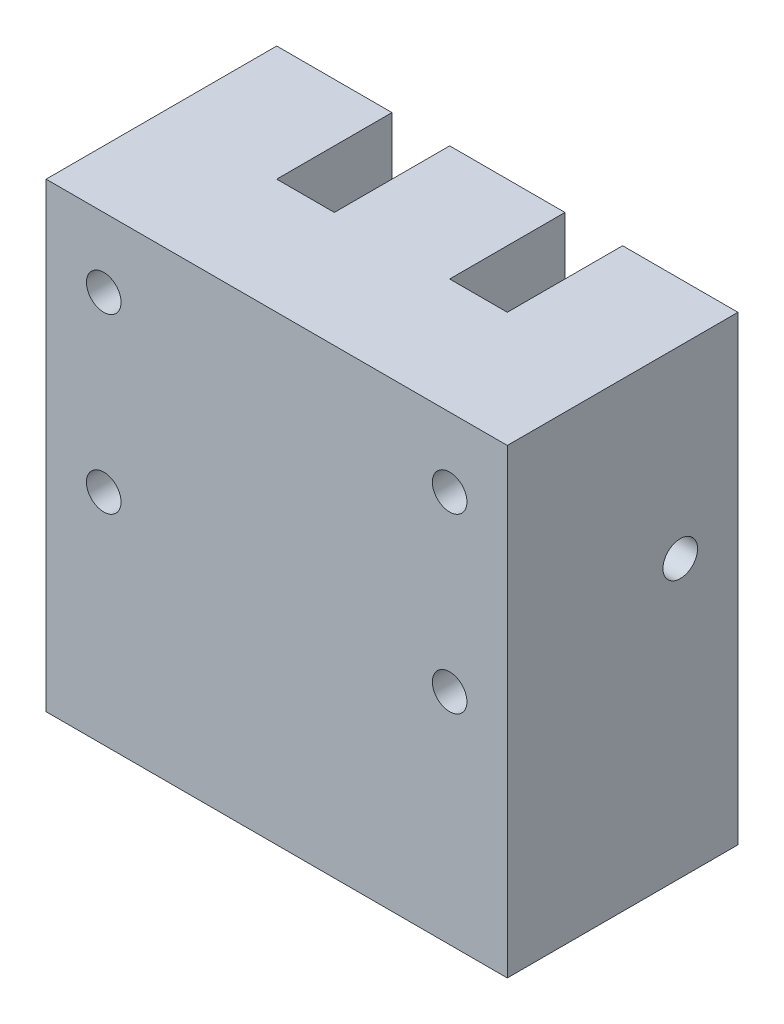
SolidWorks part; units mm, degrees
ref_plane "Front Plane" through (0, 0, 0) normal (0, 0, 1) x (1, 0, 0)
ref_plane "Top Plane" through (0, 0, 0) normal (0, 1, 0) x (1, 0, 0)
ref_plane "Right Plane" through (0, 0, 0) normal (1, 0, 0) x (0, 0, -1)
sketch "Sketch1" plane through (0, 0, 0) normal (0, 1, 0) x (1, 0, 0)
  line L0 (0, 0) -> (0, 25.4)
  line L1 (31.75, 25.4) -> (31.75, 12.7)
  line L2 (31.75, 12.7) -> (38.1, 12.7)
  line L3 (38.1, 12.7) -> (38.1, 25.4)
  line L4 (38.1, 25.4) -> (50.8, 25.4)
  line L5 (50.8, 25.4) -> (50.8, 0)
  line L6 (50.8, 0) -> (0, 0)
  line L7 (31.75, 25.4) -> (19.05, 25.4)
  line L8 (19.05, 25.4) -> (19.05, 12.7)
  line L9 (19.05, 12.7) -> (12.7, 12.7)
  line L10 (12.7, 12.7) -> (12.7, 25.4)
  line L11 (12.7, 25.4) -> (0, 25.4)
  dimension "D1" = 25.4
  dimension "D2" = 12.7
  dimension "D3" = 6.35
  dimension "D4" = 12.7
extrude "Boss-Extrude1" add sketch "Sketch1" along normal blind 50.8
sketch "Sketch2" plane through (0, 0, -25.4) normal (0, 0, -1) x (-1, 0, 0)
  line L0 (-25.4, 50.8) -> (-25.4, 0) construction
  line L1 (-31.75, 50.8) -> (-19.05, 50.8) construction
  line L2 (-31.75, 0) -> (-19.05, 0) construction
  line L3 (-50.8, 0) -> (-38.1, 0) construction
  line L4 (-50.8, 50.8) -> (-50.8, 0) construction
  circle A0 centre (-44.45, 6.35) radius 1.75
  circle A3 centre (-6.35, 6.35) radius 1.75
  dimension "D1" = 3.5
  dimension "D2" = 6.35
  dimension "D3" = 6.35
extrude "Cut-Extrude1" cut sketch "Sketch2" against normal blind 15.24
sketch "Sketch4" plane through (50.8, 0, 0) normal (1, 0, 0) x (0, 0, -1)
  line L0 (12.7, 50.8) -> (12.7, 0) construction
  line L1 (12.7, 50.8) -> (12.7, 0) construction
  line L2 (12.7, 43.2306) -> (25.4, 43.2306) construction
  line L3 (25.4, 50.8) -> (25.4, 0) construction
  line L4 (19.05, 43.2306) -> (19.05, 7.8854) construction
  line L5 (12.7, 30.48) -> (31.4115, 30.48) construction
  line L6 (0, 50.8) -> (0, 0) construction
  line L7 (0, 0) -> (25.4, 0) construction
  circle A0 centre (19.05, 30.48) radius 1.905
  dimension "D1" = 3.81
  dimension "D2" = 19.05
  dimension "D3" = 43.2306
  dimension "D4" = 30.48
extrude "Cut-Extrude2" cut sketch "Sketch4" against normal up to surface (50.8 mm away) up to face at (0, 25.4, -12.7)
sketch "Sketch5" plane through (0, 0, -25.4) normal (0, 0, -1) x (-1, 0, 0)
  line L0 (-50.8, 50.8) -> (0, 50.8) construction
  line L1 (-25.4, 50.8) -> (-25.4, 0) construction
  line L2 (-31.75, 0) -> (-19.05, 0) construction
  line L3 (-57.3245, 24.13) -> (10.6773, 24.13) construction
  line L4 (-50.8, 43.18) -> (-38.1, 43.18) construction
  line L5 (-50.8, 50.8) -> (-50.8, 0) construction
  line L6 (-38.1, 50.8) -> (-38.1, 0) construction
  line L7 (-44.45, 50.8) -> (-44.45, 0) construction
  line L8 (-50.8, 0) -> (-38.1, 0) construction
  circle A0 centre (-44.45, 24.13) radius 1.905
  circle A1 centre (-44.45, 43.18) radius 1.905
  circle A2 centre (-6.35, 24.13) radius 1.905
  circle A3 centre (-6.35, 43.18) radius 1.905
  dimension "D3" = 3.81
  dimension "D4" = 3.81
  dimension "D1" = 26.67
  dimension "D2" = 19.05
extrude "Cut-Extrude3" cut sketch "Sketch5" against normal up to surface (25.4 mm away) up to face at (25.4, 25.4, 0)
sketch "Sketch6" plane through (0, 0, 0) normal (0, -1, 0) x (1, 0, 0)
  line L0 (15.875, -6.35) -> (34.925, -6.35) construction
  line L1 (25.4, -6.35) -> (25.4, -27.1516) construction
  line L2 (0, 0) -> (50.8, 0) construction
  line L3 (50.8, 0) -> (50.8, -25.4) construction
  circle A0 centre (34.925, -6.35) radius 1.905
  circle A1 centre (15.875, -6.35) radius 1.905
  circle A2 centre (25.4, -19.05) radius 1.905
  dimension "D1" = 3.81
  dimension "D2" = 19.05
  dimension "D3" = 12.7
  dimension "D4" = 6.35
  dimension "D5" = 25.4
extrude "Cut-Extrude4" cut sketch "Sketch6" against normal blind 17.78
